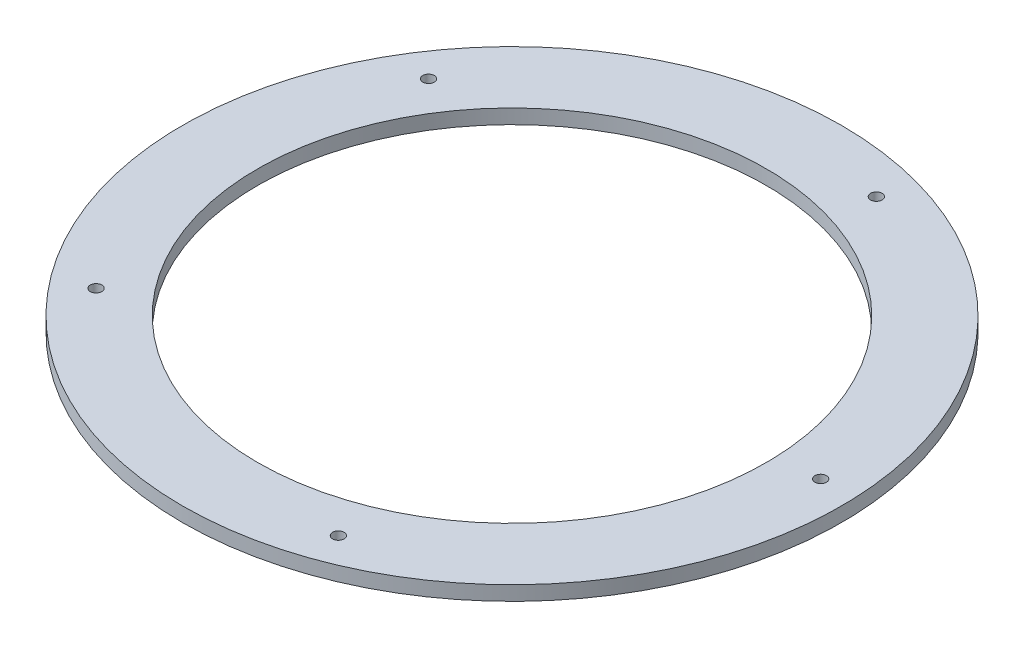
SolidWorks part; units mm, degrees
ref_plane "Front Plane" through (0, 0, 0) normal (0, 0, 1) x (1, 0, 0)
ref_plane "Top Plane" through (0, 0, 0) normal (0, 1, 0) x (1, 0, 0)
ref_plane "Right Plane" through (0, 0, 0) normal (1, 0, 0) x (0, 0, -1)
sketch "Sketch1" plane through (0, 0, 0) normal (0, 1, 0) x (1, 0, 0)
  circle A0 centre (0, 0) radius 55.88
  circle A1 centre (0, 0) radius 72.39
  dimension "D1" = 111.76
  dimension "D2" = 16.51
extrude "Boss-Extrude1" add sketch "Sketch1" along normal blind 3.175
sketch "Sketch2" plane through (0, 3.175, 0) normal (0, 1, 0) x (1, 0, 0)
  line L0 (0, 0) -> (0, 72.924) construction
  line L1 (0, 0) -> (20.8958, 75.3478) construction
  circle A0 centre (17.3769, 62.6591) radius 1.27
  circle A2 centre (0, 0) radius 55.88 construction
  circle A3 centre (0, 0) radius 72.39 construction
  dimension "D2" = 2.54
  dimension "D3" = 7.874
  dimension "D4" = 6.096
  dimension "D1" = 15.5
extrude "Cut-Extrude1" cut sketch "Sketch2" against normal through all
pattern_circular "CirPattern1" count 5 over 360 about axis through (0, 0, 0) along (0, 1, 0) of "Cut-Extrude1"
